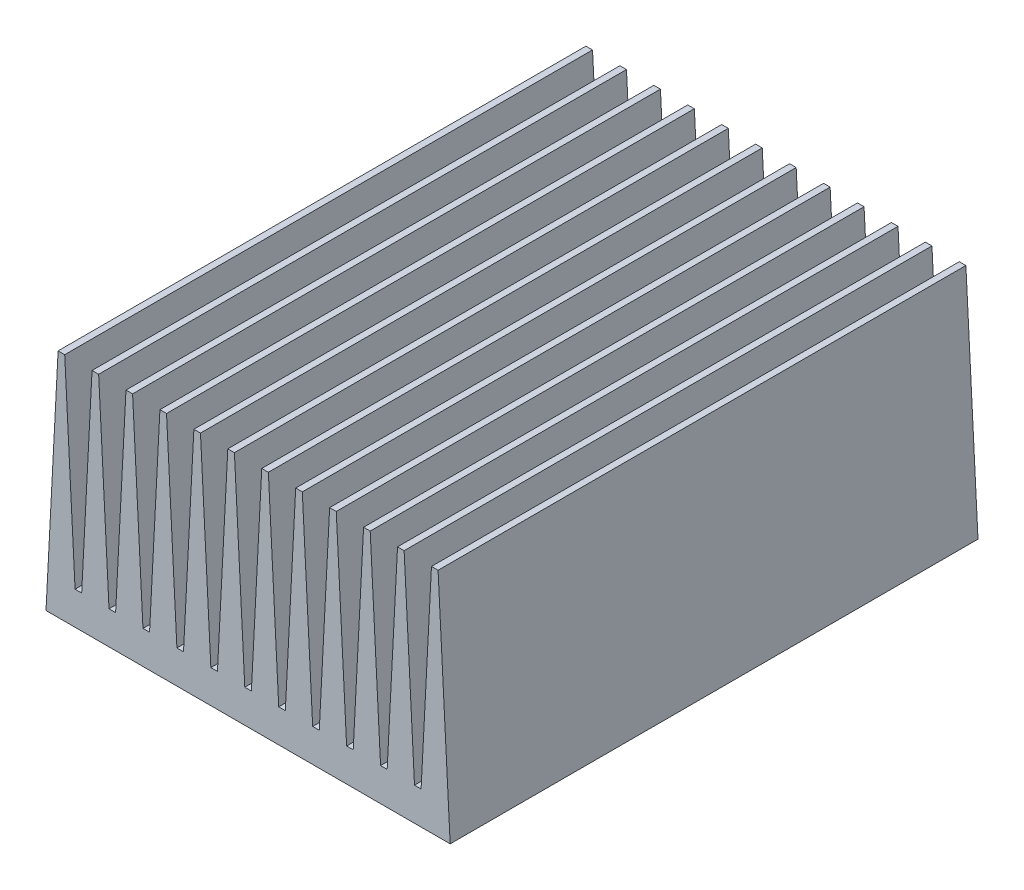
SolidWorks part; units mm, degrees
material "1060 Alloy"
ref_plane "Front Plane" through (0, 0, 0) normal (0, 0, 1) x (1, 0, 0)
ref_plane "Top Plane" through (0, 0, 0) normal (0, 1, 0) x (1, 0, 0)
ref_plane "Right Plane" through (0, 0, 0) normal (1, 0, 0) x (0, 0, -1)
sketch "Sketch1" plane through (0, 0, 0) normal (0, 0, 1) x (1, 0, 0)
  line L0 (0, 0) -> (30.6288, 0)
  line L2 (30.3668, 5) -> (28.7946, 35)
  line L3 (28.7946, 35) -> (27.7946, 35)
  line L4 (27.7946, 35) -> (26.2223, 5)
  line L5 (26.2223, 5) -> (25.2223, 5)
  line L6 (21.0779, 5) -> (20.0779, 5)
  line L7 (22.6501, 35) -> (21.0779, 5)
  line L8 (23.6501, 35) -> (22.6501, 35)
  line L9 (25.2223, 5) -> (23.6501, 35)
  line L10 (15.9334, 5) -> (14.9334, 5)
  line L11 (17.5056, 35) -> (15.9334, 5)
  line L12 (18.5056, 35) -> (17.5056, 35)
  line L13 (20.0779, 5) -> (18.5056, 35)
  line L14 (10.7889, 5) -> (9.7889, 5)
  line L15 (12.3612, 35) -> (10.7889, 5)
  line L16 (13.3612, 35) -> (12.3612, 35)
  line L17 (14.9334, 5) -> (13.3612, 35)
  line L18 (5.6445, 5) -> (4.6445, 5)
  line L19 (7.2167, 35) -> (5.6445, 5)
  line L20 (8.2167, 35) -> (7.2167, 35)
  line L21 (9.7889, 5) -> (8.2167, 35)
  line L22 (0.5, 5) -> (-0.5, 5)
  line L23 (2.0722, 35) -> (0.5, 5)
  line L24 (3.0722, 35) -> (2.0722, 35)
  line L25 (4.6445, 5) -> (3.0722, 35)
  line L26 (-4.6445, 5) -> (-5.6445, 5)
  line L27 (-3.0722, 35) -> (-4.6445, 5)
  line L28 (-2.0722, 35) -> (-3.0722, 35)
  line L29 (-0.5, 5) -> (-2.0722, 35)
  line L30 (-9.7889, 5) -> (-10.7889, 5)
  line L31 (-8.2167, 35) -> (-9.7889, 5)
  line L32 (-7.2167, 35) -> (-8.2167, 35)
  line L33 (-5.6445, 5) -> (-7.2167, 35)
  line L34 (-14.9334, 5) -> (-15.9334, 5)
  line L35 (-13.3612, 35) -> (-14.9334, 5)
  line L36 (-12.3612, 35) -> (-13.3612, 35)
  line L37 (-10.7889, 5) -> (-12.3612, 35)
  line L38 (-20.0779, 5) -> (-21.0779, 5)
  line L39 (-18.5056, 35) -> (-20.0779, 5)
  line L40 (-17.5056, 35) -> (-18.5056, 35)
  line L41 (-15.9334, 5) -> (-17.5056, 35)
  line L42 (-25.2223, 5) -> (-26.2223, 5)
  line L43 (-23.6501, 35) -> (-25.2223, 5)
  line L44 (-22.6501, 35) -> (-23.6501, 35)
  line L45 (-21.0779, 5) -> (-22.6501, 35)
  line L46 (30.3668, 5) -> (30.6288, 0)
  line L47 (-28.7946, 35) -> (-30.3668, 5)
  line L48 (-27.7946, 35) -> (-28.7946, 35)
  line L49 (-26.2223, 5) -> (-27.7946, 35)
  line L50 (0, 0) -> (-30.6288, 0)
  line L52 (-30.3668, 5) -> (-30.6288, 0)
  line L53 (-30.3668, 5) -> (-31.3668, 5) [skipped]
  dimension "D5" = 5
  dimension "D3" = 87
  dimension "D4" = 87
  dimension "D6" = 35
  dimension "D1" = 12
extrude "Boss-Extrude1" add sketch "Sketch1" against normal blind 80
equation "\"A\"= 35"
equation "\"D6@Sketch1\"=\"A\""
equation "\"C\"= 1"
equation "\"D2@Sketch1\"=\"C\""
equation "\"B\"= 80"
equation "\"D1@Boss-Extrude1\"=\"B\""
